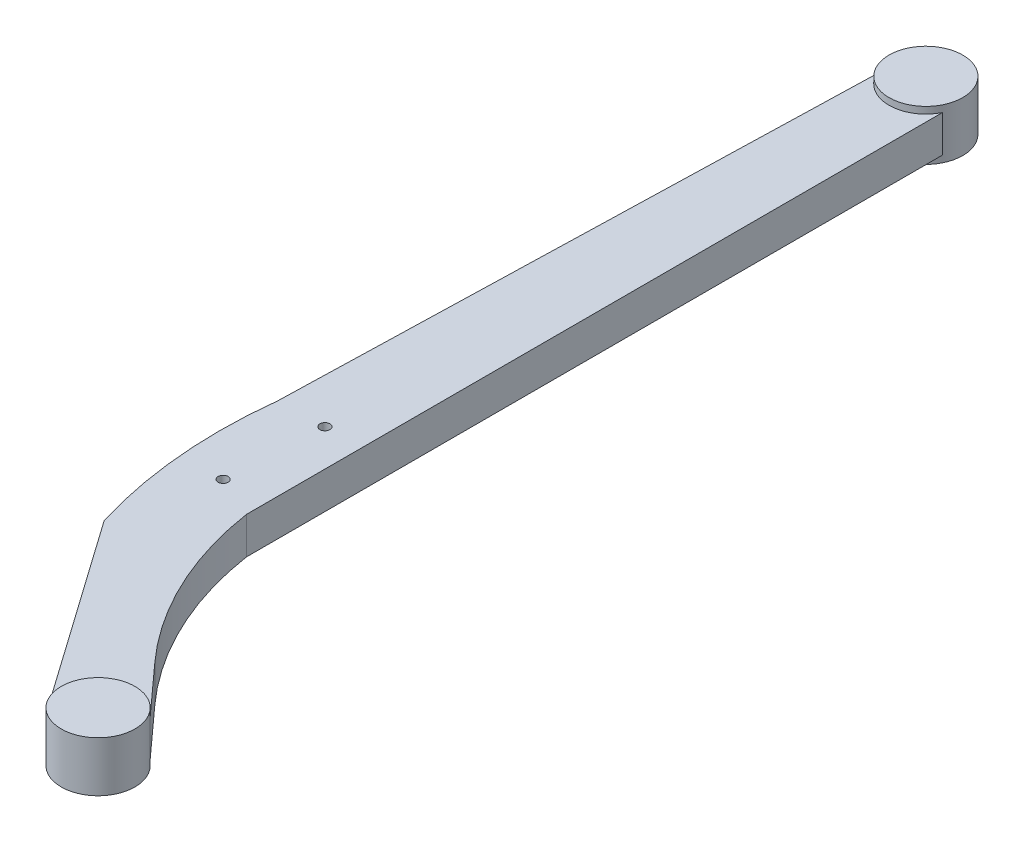
SolidWorks part; units mm, degrees
ref_plane "Front Plane" through (0, 0, 0) normal (0, 0, 1) x (1, 0, 0)
ref_plane "Top Plane" through (0, 0, 0) normal (0, 1, 0) x (1, 0, 0)
ref_plane "Right Plane" through (0, 0, 0) normal (1, 0, 0) x (0, 0, -1)
sketch "Sketch1" plane through (0, 0, 0) normal (0, 1, 0) x (1, 0, 0)
  line L10 (0, -140.9717) -> (0, 921.7826)
  line L11 (189.501, -474.1477) -> (123.7339, -401.5325)
  line L12 (108.6412, -548.7244) -> (-98.3804, -254.8026)
  line L13 (108.6412, -548.7244) -> (189.501, -474.1477)
  line L18 (0, 921.7826) -> (-98.3804, 921.7826)
  line L19 (-98.3804, 921.7826) -> (-123.4058, 28.3261)
  arc A4 (123.7339, -401.5325) -> (0, -140.9717) centre (494.33, -65.886) cw
  arc A7 (-98.3804, -254.8026) -> (-123.4058, 28.3261) centre (571.7302, -52.9021) cw
extrude "Boss-Extrude1" add sketch "Sketch1" along normal blind 55
sketch "Sketch2" plane through (0, 55, 0) normal (0, 1, 0) x (1, 0, 0)
  line L0 (108.6412, -548.7244) -> (189.501, -474.1477) construction
  line L2 (0, 921.7826) -> (-98.3804, 921.7826) construction
  circle A0 centre (149.0711, -511.436) radius 55
  circle A1 centre (-49.1902, 921.7826) radius 55
  point P10 (-49.1902, 921.7826)
extrude "Boss-Extrude2" add sketch "Sketch2" along normal blind 10 and the other way blind 65
sketch "Sketch3" plane through (0, 55, 0) normal (0, 1, 0) x (1, 0, 0)
  circle A0 centre (-54.7352, 30.7641) radius 7.5223
  circle A1 centre (-62.6233, -113.1956) radius 7.5223
extrude "Cut-Extrude1" cut sketch "Sketch3" against normal through all
